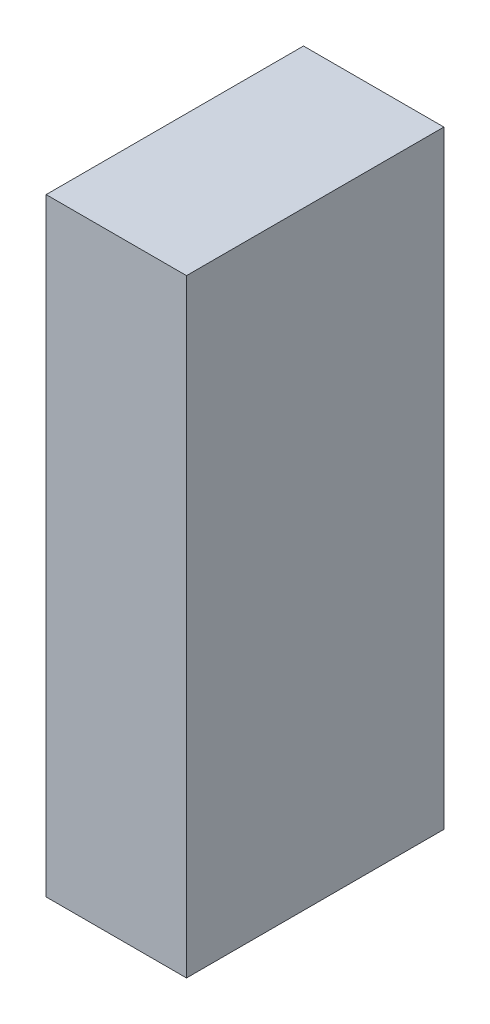
SolidWorks part; units mm, degrees
ref_plane "Front Plane" through (0, 0, 0) normal (0, 0, 1) x (1, 0, 0)
ref_plane "Top Plane" through (0, 0, 0) normal (0, 1, 0) x (1, 0, 0)
ref_plane "Right Plane" through (0, 0, 0) normal (1, 0, 0) x (0, 0, -1)
sketch "Sketch1" plane through (0, 0, 0) normal (0, 0, 1) x (1, 0, 0)
  line L1 (-300, 1300) -> (300, 1300)
  line L2 (-300, 1300) -> (-300, -1300)
  line L3 (-300, -1300) -> (300, -1300)
  line L4 (300, 1300) -> (300, -1300)
  line L5 (-300, 1300) -> (300, -1300) construction
  line L6 (-300, -1300) -> (300, 1300) construction
  point P0 (0, 0)
  dimension "D1" = 600
  dimension "D2" = 2600
extrude "Boss-Extrude1" add sketch "Sketch1" along normal blind 1100
sketch "Sketch2" plane through (0, 0, 0) normal (0, 0, -1) x (-1, 0, 0)
  line L1 (-50, -700) -> (50, -700)
  line L2 (-50, -700) -> (-50, -800)
  line L3 (-50, -800) -> (50, -800)
  line L4 (50, -700) -> (50, -800)
  line L5 (-50, -700) -> (50, -800) construction
  line L6 (-50, -800) -> (50, -700) construction
  line L7 (300, 1300) -> (300, -1300) construction
  line L9 (300, -1300) -> (-300, -1300) construction
  point P0 (0, -750)
  dimension "D1" = 100
  dimension "D2" = 100
  dimension "D3" = 250
  dimension "D4" = 500
extrude "Cut-Extrude1" cut sketch "Sketch2" against normal blind 100
